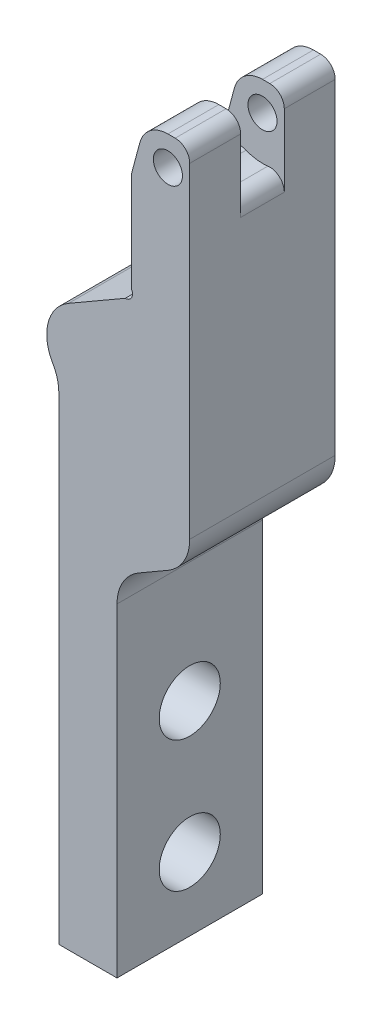
SolidWorks part; units mm, degrees
ref_plane "前视基准面" through (0, 0, 0) normal (0, 0, 1) x (1, 0, 0)
ref_plane "上视基准面" through (0, 0, 0) normal (0, 1, 0) x (1, 0, 0)
ref_plane "右视基准面" through (0, 0, 0) normal (1, 0, 0) x (0, 0, -1)
sketch "草图1" plane through (0, 0, 0) normal (0, 0, 1) x (1, 0, 0)
  line L0 (-5.9282, 37) -> (-4, 33.6603)
  line L1 (-5.9282, 37) -> (1, 41)
  line L2 (1, 41) -> (1, 52)
  line L3 (-4, 33.6603) -> (-4, 0)
  line L4 (-4, 0) -> (0, 0)
  line L5 (0, 0) -> (0, 24)
  line L6 (0, 24) -> (5, 26.8868)
  line L7 (5, 26.8868) -> (5, 52)
  line L8 (5, 52) -> (1, 52)
  point P7 (-88.813, 80)
  point P10 (-95.7217, 93.4168)
  point P11 (-98.238, 127.492)
  point P12 (-93.5438, 114.5743)
  point P13 (-99.388, 100)
  point P14 (-99.388, 80)
  point P15 (-98.238, 116.5224)
  point P16 (-103.1716, 103.3257)
  point P17 (-100.534, 103.0652)
  point P18 (-99.388, 80)
  point P19 (0, 0)
  dimension "D1" = 11
  dimension "D2" = 4
  dimension "D3" = 60
  dimension "D4" = 5
  dimension "D5" = 28
  dimension "D6" = 24
  dimension "D7" = 8
extrude "凸台-拉伸1" add sketch "草图1" along normal mid plane 10
sketch "草图2" plane through (0, 0, 0) normal (1, 0, 0) x (0, 0, -1)
  line L0 (0, 0) -> (0, 14) construction
  line L1 (-5, 0) -> (5, 0) construction
  circle A0 centre (0, 14) radius 2.1
  circle A1 centre (0, 5) radius 2.1
  point P7 (0, 0)
  point P8 (-6, 14.9064)
  point P9 (-6, 5)
  dimension "D1" = 4.2
  dimension "D2" = 9
  dimension "D3" = 5
extrude "切除-拉伸1" cut sketch "草图2" against normal through all
sketch "草图3" plane through (0, 0, 5) normal (0, 0, 1) x (1, 0, 0)
  line L0 (3.5, 50) -> (3.5, 52) construction
  line L1 (3.5, 52) -> (5, 52)
  line L2 (1, 52) -> (1, 41) construction
  line L4 (1, 48.3973) -> (1, 52.5)
  line L5 (1, 52.5) -> (5, 52.5)
  line L6 (5, 52.5) -> (5, 52)
  line L7 (0.567, 41.25) -> (1, 41.25) construction
  line L8 (0.567, 41.25) -> (0.7835, 40.875) construction
  line L9 (1, 41) -> (-5.9282, 37) construction
  line L10 (5, 52) -> (1, 52) construction
  line L11 (1.5681, 50.5176) -> (1, 48.3973)
  circle A0 centre (3.5, 50) radius 1
  circle A1 centre (3.5, 50) radius 2.5 construction
  circle A3 centre (0.567, 41.25) radius 0.5
  arc A4 (1.5681, 50.5176) -> (3.5, 52) centre (3.5, 50) cw
  point P21 (3.4652, 51.9997)
  dimension "D1" = 2
  dimension "D2" = 5
  dimension "D4" = 1.5
  dimension "D5" = 1
  dimension "D3" = 2
  dimension "D7" = 15
extrude "切除-拉伸2" cut sketch "草图3" against normal through all
sketch "草图4" plane through (0, 0, 0) normal (0, 0, 1) x (1, 0, 0)
  circle A0 centre (3.5, 50) radius 3
  dimension "D1" = 6
extrude "切除-拉伸3" cut sketch "草图4" against normal mid plane 3
fillet "圆角1" radius 3 4 edges at (-5.9282, 37, 0) (-4, 33.6603, 0) (0, 24, 0) (5, 26.8868, 0)
fillet "圆角4" radius 1 4 edges at (5, 52, -3.25) (5, 52, 3.25) (1, 48.3417, 0) (5, 47.4019, 0)
